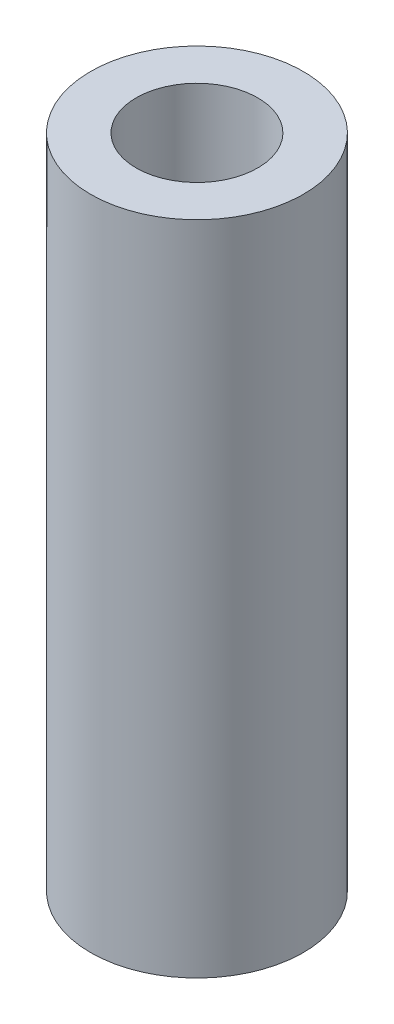
SolidWorks part; units mm, degrees
ref_plane "Front Plane" through (0, 0, 0) normal (0, 0, 1) x (1, 0, 0)
ref_plane "Top Plane" through (0, 0, 0) normal (0, 1, 0) x (1, 0, 0)
ref_plane "Right Plane" through (0, 0, 0) normal (1, 0, 0) x (0, 0, -1)
sketch "Sketch1" plane through (0, 0, 0) normal (0, 1, 0) x (1, 0, 0)
  circle A0 centre (0, 0) radius 2.54
  circle A1 centre (0, 0) radius 4.445
  dimension "D1" = 5.08
  dimension "D2" = 8.89
extrude "Boss-Extrude1" add sketch "Sketch1" along normal blind 27.432
